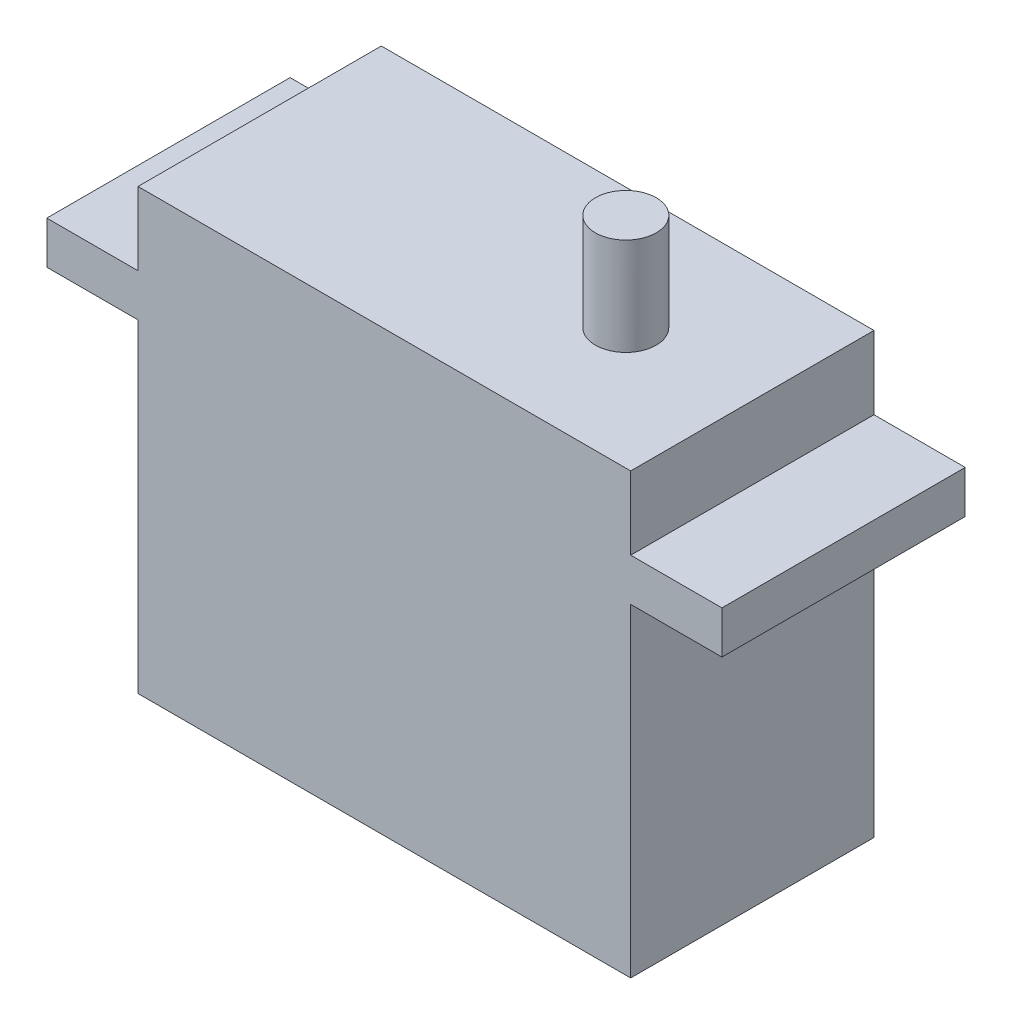
SolidWorks part; units mm, degrees
ref_plane "Front Plane" through (0, 0, 0) normal (0, 0, 1) x (1, 0, 0)
ref_plane "Top Plane" through (0, 0, 0) normal (0, 1, 0) x (1, 0, 0)
ref_plane "Right Plane" through (0, 0, 0) normal (1, 0, 0) x (0, 0, -1)
sketch "Sketch1" plane through (0, 0, 0) normal (0, 1, 0) x (1, 0, 0)
  line L1 (-27.75, -10) -> (27.75, -10)
  line L2 (-27.75, -10) -> (-27.75, 10)
  line L3 (-27.75, 10) -> (27.75, 10)
  line L4 (27.75, -10) -> (27.75, 10)
  line L5 (-27.75, -10) -> (27.75, 10) construction
  line L6 (-27.75, 10) -> (27.75, -10) construction
  point P0 (0, 0)
  dimension "D1" = 55.5
  dimension "D2" = 20
extrude "Boss-Extrude1" add sketch "Sketch1" along normal blind 36.1
sketch "Sketch2" plane through (0, 0, 0) normal (0, -1, 0) x (1, 0, 0)
  line L0 (27.75, -10) -> (-27.75, -10) construction
  line L1 (27.75, 10) -> (20.25, 10)
  line L2 (27.75, 10) -> (27.75, -10)
  line L3 (27.75, -10) -> (20.25, -10)
  line L4 (20.25, 10) -> (20.25, -10)
  line L5 (27.75, 10) -> (20.25, -10) construction
  line L6 (27.75, -10) -> (20.25, 10) construction
  line L7 (-27.75, 10) -> (27.75, 10) construction
  line L8 (-27.75, -10) -> (-20.25, -10)
  line L9 (-27.75, -10) -> (-27.75, 10)
  line L10 (-27.75, 10) -> (-20.25, 10)
  line L11 (-20.25, -10) -> (-20.25, 10)
  line L12 (-27.75, -10) -> (-20.25, 10) construction
  line L13 (-27.75, 10) -> (-20.25, -10) construction
  point P4 (24, 0)
  point P12 (-24, 0)
  dimension "D1" = 7.5
  dimension "D2" = 7.5
extrude "Cut-Extrude1" cut sketch "Sketch2" against normal blind 26.6
sketch "Sketch3" plane through (0, 36.1, 0) normal (0, 1, 0) x (1, 0, 0)
  line L1 (27.75, 10) -> (20.25, 10)
  line L2 (27.75, 10) -> (27.75, -10)
  line L3 (27.75, -10) -> (20.25, -10)
  line L4 (20.25, 10) -> (20.25, -10)
  line L5 (27.75, 10) -> (20.25, -10) construction
  line L6 (27.75, -10) -> (20.25, 10) construction
  line L7 (-27.75, 10) -> (-20.25, 10)
  line L8 (-27.75, 10) -> (-27.75, -10)
  line L9 (-27.75, -10) -> (-20.25, -10)
  line L10 (-20.25, 10) -> (-20.25, -10)
  line L11 (-27.75, 10) -> (-20.25, -10) construction
  line L12 (-27.75, -10) -> (-20.25, 10) construction
  point P4 (24, 0)
  point P11 (-24, 0)
extrude "Cut-Extrude2" cut sketch "Sketch3" against normal blind 6
sketch "Sketch4" plane through (0, 36.1, 0) normal (0, 1, 0) x (1, 0, 0)
  line L0 (20.25, 10) -> (20.25, -10) construction
  line L1 (20.25, 10) -> (-20.25, 10) construction
  circle A0 centre (9.85, 0) radius 2.5
  dimension "D2" = 5
  dimension "D1" = 10.4
  dimension "D3" = 10
extrude "Boss-Extrude2" add sketch "Sketch4" along normal blind 8
